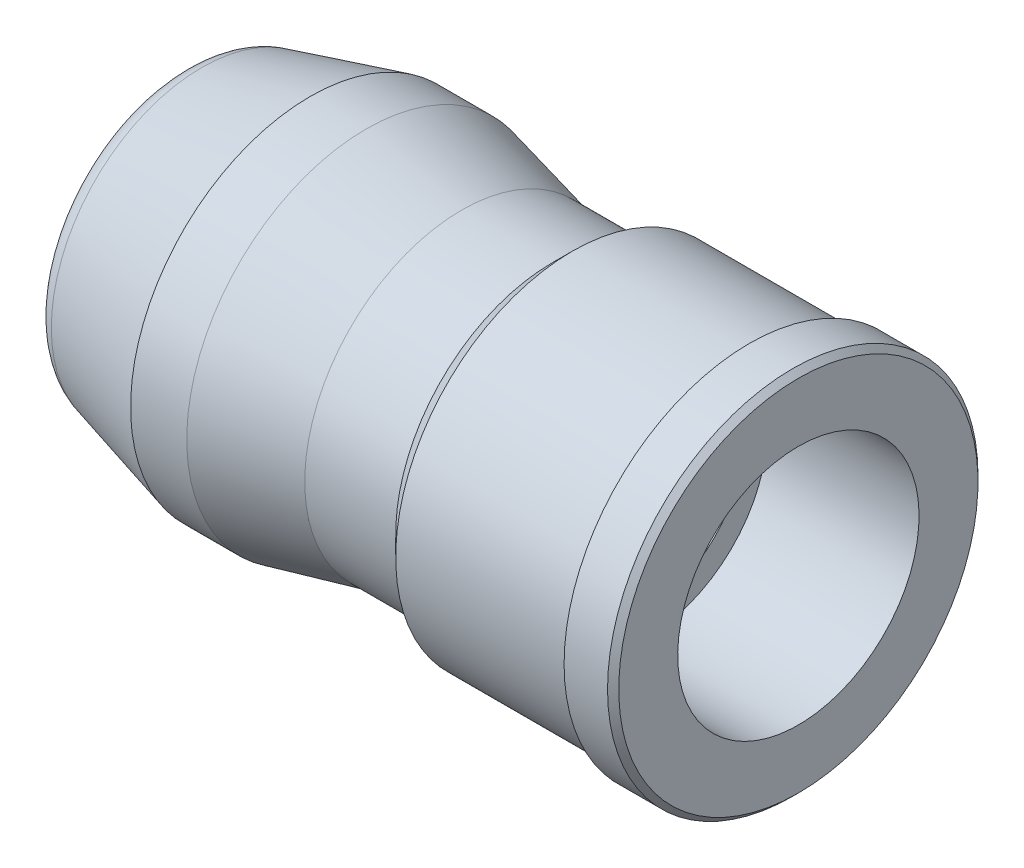
SolidWorks part; units mm, degrees
ref_plane "Front Plane" through (0, 0, 0) normal (0, 0, 1) x (1, 0, 0)
ref_plane "Top Plane" through (0, 0, 0) normal (0, 1, 0) x (1, 0, 0)
ref_plane "Right Plane" through (0, 0, 0) normal (1, 0, 0) x (0, 0, -1)
sketch "Sketch1" plane through (0, 0, 0) normal (0, 0, 1) x (1, 0, 0)
  line L0 (0, 0) -> (0, 2.58)
  line L1 (0, 2.58) -> (2.3, 3.1963)
  line L2 (2.3, 3.1963) -> (3.3, 3.1963)
  line L3 (3.3, 3.1963) -> (5, 2.7939)
  line L4 (5, 2.7939) -> (6.62, 2.7939)
  line L5 (6.62, 2.7939) -> (6.9761, 3.15)
  line L6 (6.9761, 3.15) -> (10.1261, 3.15)
  line L7 (10.1261, 3.15) -> (10.1261, 3.3)
  line L8 (10.1261, 3.3) -> (11, 3.3)
  line L9 (11, 3.3) -> (11, 2.15)
  line L10 (11, 2.15) -> (8.3, 2.15)
  line L11 (8.3, 2.15) -> (8.3, 0)
  line L12 (8.3, 0) -> (0, 0)
  dimension "D1" = 105
  dimension "D2" = 135
  dimension "D3" = 1.15
  dimension "D4" = 2.58
  dimension "D5" = 2.15
  dimension "D6" = 1
  dimension "D7" = 8.3
  dimension "D8" = 2.7
  dimension "D9" = 3.15
  dimension "D10" = 1.62
  dimension "D11" = 1.7
  dimension "D12" = 1
  dimension "D13" = 2.3
revolve "Revolve1" add sketch "Sketch1" angle 360 about L12
sketch "Sketch3" plane through (0, 0, 0) normal (-1, 0, 0) x (0, 0, 1)
  circle A0 centre (0, 0) radius 1.7068
extrude "Cut-Extrude1" cut sketch "Sketch3" against normal blind 10
sketch "Sketch4" plane through (0, 0, 0) normal (-1, 0, 0) x (0, 0, 1)
  circle A0 centre (0, 0) radius 2.0502
extrude "Cut-Extrude2" cut sketch "Sketch4" against normal blind 0.5
fillet "Fillet1" radius 0.5 1 edges at (0, 2.58, 0)
chamfer "Chamfer1" distance 0.1 angle 45 2 edges at (11, 3.3, 0) (10.1261, 3.15, 0)
